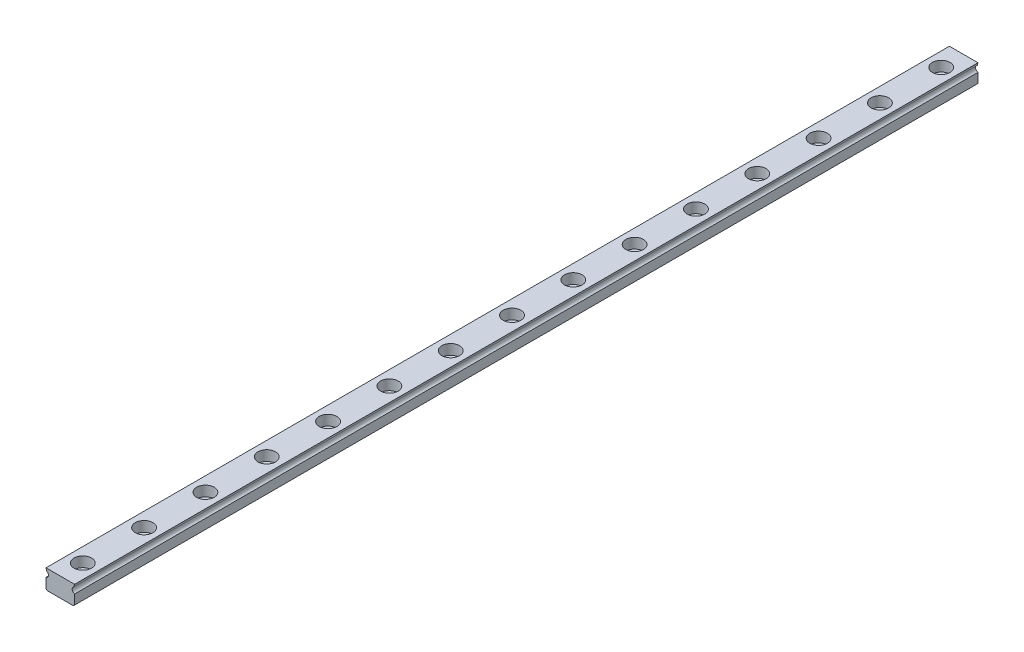
SolidWorks part; units mm, degrees
ref_plane "Front Plane" through (0, 0, 0) normal (0, 0, 1) x (1, 0, 0)
ref_plane "Top Plane" through (0, 0, 0) normal (0, 1, 0) x (1, 0, 0)
ref_plane "Right Plane" through (0, 0, 0) normal (1, 0, 0) x (0, 0, -1)
sketch "Sketch1" plane through (0, 0, 0) normal (0, 0, 1) x (1, 0, 0)
  line L0 (3.5, 4.7) -> (-3.5, 4.7)
  line L1 (-3.5, 4.7) -> (-3.3339, 4.0801)
  line L2 (-3.5, 2.6652) -> (-3.5, 0)
  line L3 (-3.5, 0) -> (3.5, 0)
  line L4 (3.5, 0) -> (3.5, 2.6652)
  line L5 (3.3339, 4.0801) -> (3.5, 4.7)
  arc A0 (-3.3339, 4.0801) -> (-3.5, 2.6652) centre (-3.65, 3.4) cw
  arc A1 (3.5, 2.6652) -> (3.3339, 4.0801) centre (3.65, 3.4) cw
extrude "Boss-Extrude1" add sketch "Sketch1" against normal blind 221
hole_wizard "CBORE for M2 Hex Head Machine Screw1" positions "Sketch3" profile "Sketch2" counterbore size "M2" standard "ANSI Metric"
sketch "Sketch3" plane through (0, 4.7, 0) normal (0, 1, 0) x (-1, 0, 0)
  point P0 (0, -5.5)
  point P1 (0, -20.5)
  point P2 (0, -35.5)
  point P3 (0, -50.5)
  point P4 (0, -65.5)
  point P5 (0, -80.5)
  point P6 (0, -95.5)
  point P7 (0, -110.5)
  point P8 (0, -125.5)
  point P9 (0, -140.5)
  point P10 (0, -155.5)
  point P11 (0, -170.5)
  point P12 (0, -185.5)
  point P13 (0, -200.5)
  point P14 (0, -215.5)
sketch "Sketch2" plane through (0, 4.7, -5.5) normal (1, 0, 0) x (0, 0, 1)
  line L0 (0, 0) -> (0, 4.7)
  line L1 (0, 4.7) -> (1.25, 4.7)
  line L3 (1.25, 4.7) -> (1.25, 2.5)
  line L4 (1.25, 2.5) -> (2.15, 2.5)
  line L5 (2.15, 2.5) -> (2.15, 0)
  line L7 (2.15, 0) -> (0, 0)
  line L11 (0, -6.35) -> (0, 107.95) construction
  dimension "Thru Hole Dia." = 2.5
  dimension "Thru Hole Depth" = 4.7
  dimension "C'Bore Dia." = 4.3
  dimension "C'Bore Depth" = 2.5
chamfer "Chamfer1" distance 0.3 angle 45 2 edges at (-3.5, 0, -110.5) (3.5, 0, -110.5)
